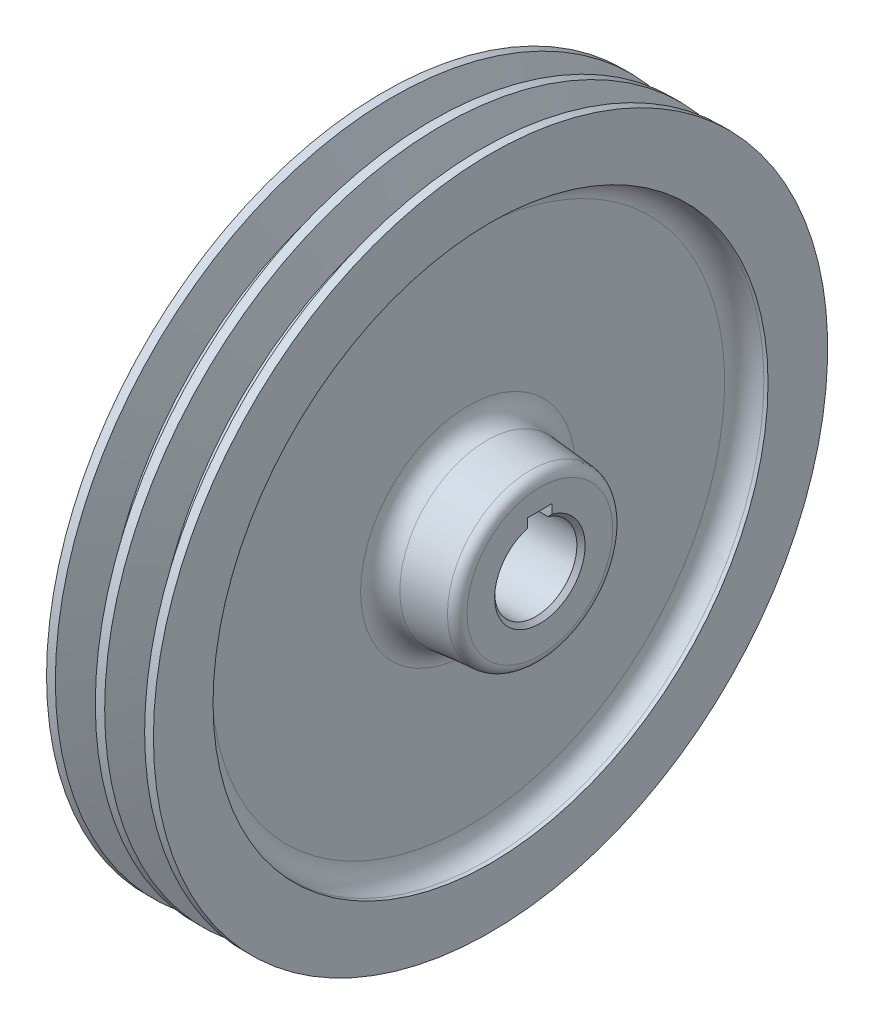
SolidWorks part; units mm, degrees
ref_plane "前视基准面" through (0, 0, 0) normal (0, 0, 1) x (1, 0, 0)
ref_plane "上视基准面" through (0, 0, 0) normal (0, 1, 0) x (1, 0, 0)
ref_plane "右视基准面" through (0, 0, 0) normal (1, 0, 0) x (0, 0, -1)
sketch "草图1" plane through (0, 0, 0) normal (0, 0, 1) x (1, 0, 0)
  line L0 (0, 0) -> (64.8368, 0) construction
  line L1 (-12, 10) -> (-12, 20)
  line L2 (0, 82) -> (26, 82)
  line L3 (26, 82) -> (26, 67.5)
  line L4 (-12, 20) -> (-41, 20) construction
  line L5 (5.5, 21.5311) -> (5.5, 67.0188)
  line L6 (38, 10) -> (-12, 10)
  line L7 (2.1385, 82) -> (4.8901, 73) construction
  line L8 (4.8901, 73) -> (9.1099, 73) construction
  line L9 (9.1099, 73) -> (11.8615, 82) construction
  line L10 (0, 80) -> (26, 80) construction
  line L11 (7, 73) -> (7, 10) construction
  line L12 (44, 67.5) -> (0, 67.5) construction
  line L13 (26, 67.5) -> (79, 67.5) construction
  line L14 (20.5, 67.0188) -> (20.5, 21.5311)
  line L15 (-6, 20) -> (38, 20) construction
  line L16 (13, 10) -> (13, 82) construction
  line L17 (38, 20) -> (38, 10)
  line L18 (0, 67.5) -> (0, 82)
  line L19 (5.5, 60.5) -> (20.5, 60.5) construction
  line L20 (5.5, 27) -> (20.5, 27) construction
  line L21 (26, 67.5) -> (26, 60.5) construction
  line L22 (26, 60.5) -> (20.5, 60.5) construction
  line L23 (20.5, 27) -> (38, 27) construction
  line L24 (38, 27) -> (38, 20) construction
  line L25 (20.5, 67.0188) -> (26, 67.5)
  line L26 (5.5, 67.0188) -> (0, 67.5)
  line L27 (5.5, 21.5311) -> (-12, 20)
  line L28 (20.5, 21.5311) -> (38, 20)
  point P17 (2.75, 80)
  point P18 (11.25, 80)
  dimension "d2" = 135
  dimension "L" = 50
  dimension "B" = 26
  dimension "d" = 20
  dimension "d1" = 40
  dimension "D3" = 5
  dimension "D4" = 5
  dimension "dd" = 160
  dimension "f" = 7
  dimension "槽轮角" = 34
  dimension "bd" = 8.5
  dimension "hf" = 7
  dimension "ha" = 2
  dimension "da" = 164
  dimension "S" = 15
  dimension "S2" = 7
revolve "旋转1" add sketch "草图1" angle 360 about L0
sketch "草图2" plane through (0, 0, 0) normal (0, 0, 1) x (1, 0, 0)
  line L0 (9.1099, 73) -> (11.8615, 82) construction
  line L1 (4.8901, 73) -> (9.1099, 73) construction
  line L2 (2.1385, 82) -> (4.8901, 73) construction
  line L3 (9.1099, 73) -> (11.8615, 82)
  line L4 (4.8901, 73) -> (9.1099, 73)
  line L5 (2.1385, 82) -> (4.8901, 73)
  line L6 (2.1385, 82) -> (11.8615, 82)
  line L7 (0, 0) -> (123, 0) construction
revolve "切除-旋转1" cut sketch "草图2" angle 360 about L7
pattern_linear "轮槽数" count 2 spacing 12 along (1, 0, 0) of "切除-旋转1"
chamfer "倒角1" distance 1 2 edges at (-12, 0, 10) (38, 0, 10)
sketch "草图4" plane through (-12, 0, 0) normal (-1, 0, 0) x (0, 0, 1)
  line L1 (-3, 9.5394) -> (3, 9.5394)
  line L2 (-3, 9.5394) -> (-3, 12.8)
  line L3 (-3, 12.8) -> (3, 12.8)
  line L4 (3, 9.5394) -> (3, 12.8)
  circle A0 centre (0, 0) radius 10 construction
  point P6 (0.2, 12.8)
  dimension "键槽高度" = 12.8
  dimension "键槽宽度" = 6
  dimension "t1" = 2.8
extrude "切除-拉伸1" cut sketch "草图4" against normal through all
fillet "圆角1" radius 5 4 edges at (20.5, 0, 67.0188) (5.5, 0, 21.5311) (5.5, 0, 67.0188) (20.5, 0, 21.5311)
fillet "圆角2" radius 2.5 2 edges at (38, 0, 20) (-12, 0, 20)
sketch "草图5" plane through (0, 0, 0) normal (1, 0, 0) x (0, 0, -1)
  line L0 (0, 73) -> (0, 10) construction
  circle A0 centre (0, 43.75) radius 16.75
